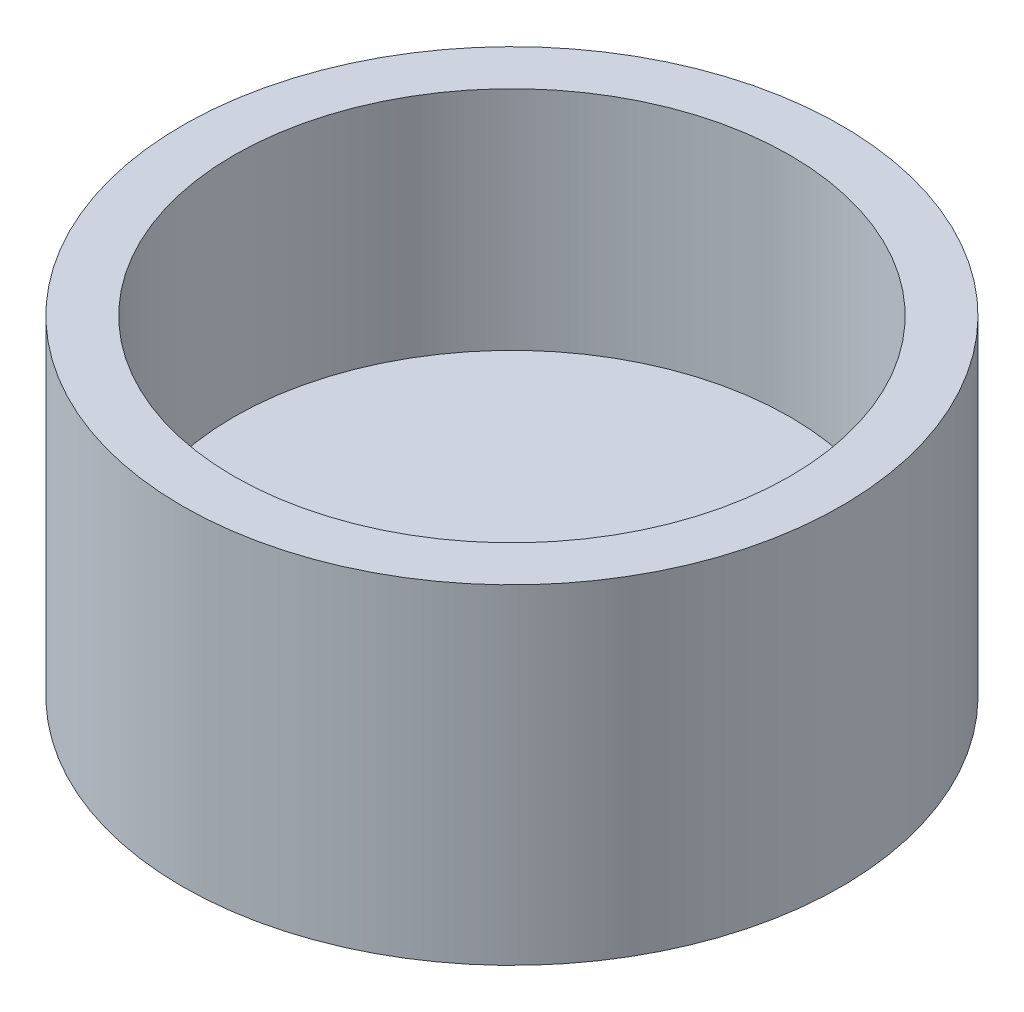
SolidWorks part; units mm, degrees
ref_plane "Front Plane" through (0, 0, 0) normal (0, 0, 1) x (1, 0, 0)
ref_plane "Top Plane" through (0, 0, 0) normal (0, 1, 0) x (1, 0, 0)
ref_plane "Right Plane" through (0, 0, 0) normal (1, 0, 0) x (0, 0, -1)
sketch "Sketch1" plane through (0, 0, 0) normal (0, 1, 0) x (1, 0, 0)
  circle A0 centre (0, 0) radius 16
  dimension "D1" = 32
extrude "Boss-Extrude1" add sketch "Sketch1" along normal blind 16
sketch "Sketch2" plane through (0, 16, 0) normal (0, 1, 0) x (1, 0, 0)
  circle A0 centre (0, 0) radius 13.5
  dimension "D1" = 27
extrude "Cut-Extrude1" cut sketch "Sketch2" against normal offset from surface (11 mm away) 5 up to face at (0, 0, 16)
